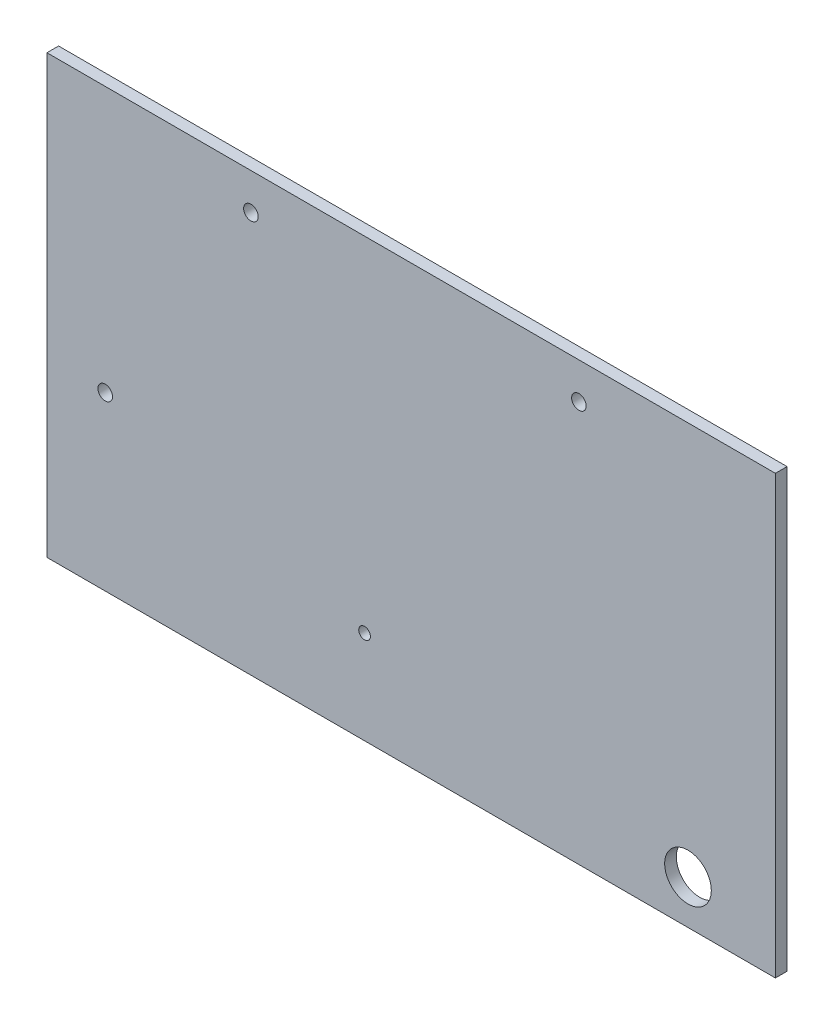
SolidWorks part; units mm, degrees
ref_plane "Front Plane" through (0, 0, 0) normal (0, 0, 1) x (1, 0, 0)
ref_plane "Top Plane" through (0, 0, 0) normal (0, 1, 0) x (1, 0, 0)
ref_plane "Right Plane" through (0, 0, 0) normal (1, 0, 0) x (0, 0, -1)
sketch "Sketch1" plane through (0, 0, 0) normal (0, 0, 1) x (1, 0, 0)
  line L1 (-112.8247, 64.3669) -> (137.1753, 64.3669)
  line L2 (-112.8247, 64.3669) -> (-112.8247, -85.6331)
  line L3 (-112.8247, -85.6331) -> (137.1753, -85.6331)
  line L4 (137.1753, 64.3669) -> (137.1753, -85.6331)
  dimension "D1" = 250
  dimension "D2" = 150
extrude "Boss-Extrude1" add sketch "Sketch1" along normal blind 4
sketch "Sketch2" plane through (0, 0, 4) normal (0, 0, 1) x (1, 0, 0)
  line L0 (137.1753, -70.6331) -> (107.1753, -70.6331) construction
  line L1 (137.1753, -85.6331) -> (137.1753, 64.3669) construction
  line L2 (107.1753, -85.6331) -> (107.1753, -70.6331) construction
  line L3 (-112.8247, -85.6331) -> (137.1753, -85.6331) construction
  circle A0 centre (107.1753, -70.6331) radius 8
extrude "Cut-Extrude1" cut sketch "Sketch2" against normal blind 4
sketch "Sketch3" plane through (0, 0, 0) normal (0, 0, -1) x (-1, 0, 0)
  line L0 (37.8247, 54.3669) -> (83.6677, 54.3669) construction
  line L1 (37.8247, 54.3669) -> (97.8247, 54.3669) construction
  line L2 (37.8247, 54.3669) -> (37.8247, -30.6331) construction
  line L3 (37.8247, -30.6331) -> (97.8247, -30.6331) construction
  line L4 (97.8247, 54.3669) -> (97.8247, -30.6331) construction
  line L5 (37.8247, 54.3669) -> (97.8247, -30.6331) construction
  line L6 (37.8247, -30.6331) -> (97.8247, 54.3669) construction
  line L7 (83.6677, 54.3669) -> (88.6677, 54.3669) construction
  line L8 (97.8247, 54.3669) -> (30.5897, 54.3669) construction
  line L9 (30.5897, 54.3669) -> (55.0597, 54.3669) construction
  line L10 (42.8247, 54.3669) -> (42.8247, 49.3669) construction
  line L11 (97.8247, -30.6331) -> (92.8247, -30.6331) construction
  line L12 (92.8247, -30.6331) -> (92.8247, -26.6331) construction
  line L13 (-73.7391, 54.3669) -> (-69.7391, 54.3669) construction
  line L14 (-73.7391, 54.3669) -> (7.8247, 54.3669) construction
  line L15 (-73.7391, 54.3669) -> (-73.7391, -55.6331) construction
  line L16 (-73.7391, -55.6331) -> (7.8247, -55.6331) construction
  line L17 (7.8247, 54.3669) -> (7.8247, -55.6331) construction
  line L18 (-73.7391, 54.3669) -> (7.8247, -55.6331) construction
  line L19 (-73.7391, -55.6331) -> (7.8247, 54.3669) construction
  line L20 (-69.7391, 54.3669) -> (-69.7391, 49.3669) construction
  line L21 (7.8247, -55.6331) -> (3.8247, -55.6331) construction
  line L22 (3.8247, -55.6331) -> (3.8247, -51.6331) construction
  line L23 (-137.1753, 64.3669) -> (112.8247, 64.3669) construction
  line L24 (112.8247, 64.3669) -> (112.8247, -85.6331) construction
  circle A0 centre (42.8247, 51.8669) radius 2.5
  circle A1 centre (92.8247, -26.6331) radius 2.5
  circle A2 centre (-69.7391, 51.8669) radius 2.5
  circle A3 centre (3.8247, -53.6331) radius 2
  point P4 (67.8247, 11.8669)
  point P20 (-32.9572, -0.6331)
  dimension "D3" = 5
  dimension "D9" = 5
  dimension "D1" = 85
  dimension "D2" = 60
  dimension "D4" = 78.5
  dimension "D5" = 4
  dimension "D6" = 105.5
  dimension "D7" = 5
  dimension "D8" = 2.5
  dimension "D10" = 4
  dimension "D11" = 2.5
  dimension "D12" = 4
  dimension "D13" = 2
  dimension "D14" = 10
  dimension "D15" = 10
  dimension "D16" = 30
  dimension "D17" = 15
extrude "Cut-Extrude2" cut sketch "Sketch3" against normal blind 4
